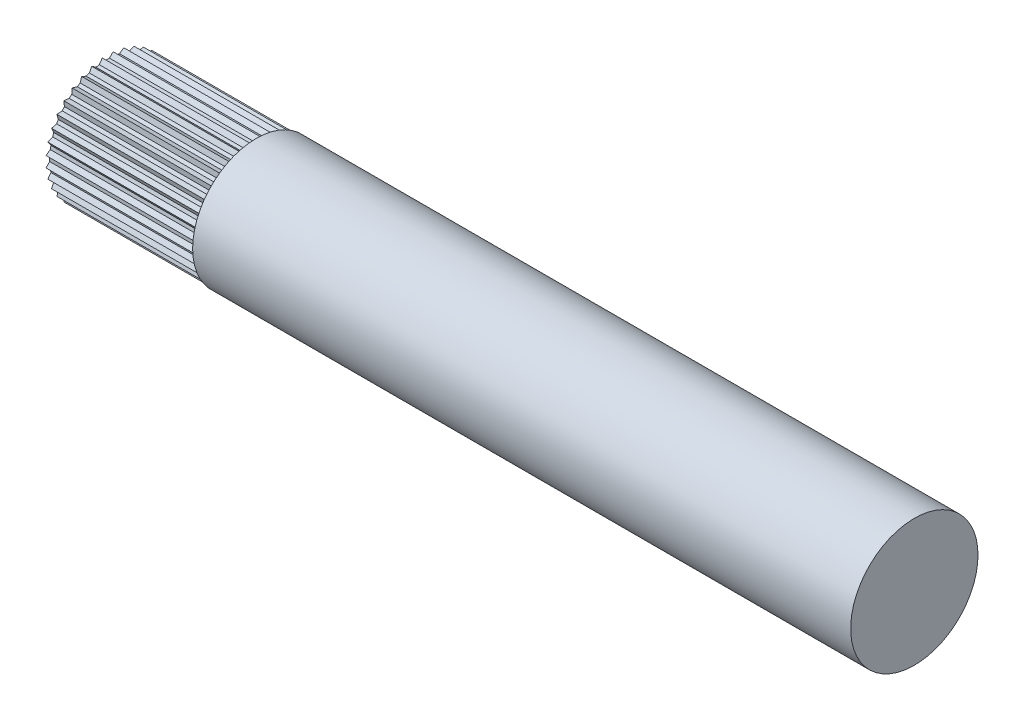
SolidWorks part; units mm, degrees
material "AISI 1015 Steel, Cold Drawn (SS)"
ref_plane "X-Y Datum" through (0, 0, 0) normal (0, 0, 1) x (1, 0, 0)
ref_plane "X-Z Datum" through (0, 0, 0) normal (0, 1, 0) x (1, 0, 0)
ref_plane "Y-Z Datum" through (0, 0, 0) normal (1, 0, 0) x (0, 0, -1)
sketch "Sketch1" plane through (0, 0, 0) normal (0, 1, 0) x (1, 0, 0)
  line L0 (139.925, 9.525) -> (139.925, 7.9375)
  line L1 (139.925, 7.9375) -> (19.25, 7.9375)
  line L2 (19.25, 7.9375) -> (19.25, 9.525)
  line L3 (19.25, 9.525) -> (139.925, 9.525)
  line L6 (157.324, 0) -> (-11.2643, 0) construction
  line L7 (19.25, 9.525) -> (19.25, -9.525) construction
  dimension "D1" = 1.5875
revolve "Revolve1" add sketch "Sketch1" angle 360 about L6
sketch "Sketch4" plane through (0, 0, 0) normal (1, 0, 0) x (0, 0, -1)
  line L0 (-9.2357, 0.808) -> (-8.6817, 0.254)
  line L1 (-8.6817, 0.254) -> (-8.6817, -0.254)
  line L2 (-8.6817, -0.254) -> (-9.2357, -0.808)
  line L3 (-8.6817, 0) -> (0, 0) construction
  line L4 (-8.5939, 1.2574) -> (-9.2357, 0.808)
  line L5 (-8.5057, 1.7577) -> (-8.5939, 1.2574)
  line L6 (-8.9551, 2.3995) -> (-8.5057, 1.7577)
  line L7 (-8.245, 2.7306) -> (-8.9551, 2.3995)
  line L8 (-8.0713, 3.208) -> (-8.245, 2.7306)
  line L9 (-8.4024, 3.9181) -> (-8.0713, 3.208)
  line L10 (-7.6456, 4.1209) -> (-8.4024, 3.9181)
  line L11 (-7.3916, 4.5608) -> (-7.6456, 4.1209)
  line L12 (-7.5944, 5.3176) -> (-7.3916, 4.5608)
  line L13 (-6.8138, 5.3859) -> (-7.5944, 5.3176)
  line L14 (-6.4873, 5.7751) -> (-6.8138, 5.3859)
  line L15 (-6.5556, 6.5556) -> (-6.4873, 5.7751)
  line L16 (-5.7751, 6.4873) -> (-6.5556, 6.5556)
  line L17 (-5.3859, 6.8138) -> (-5.7751, 6.4873)
  line L18 (-5.3176, 7.5944) -> (-5.3859, 6.8138)
  line L19 (-4.5608, 7.3916) -> (-5.3176, 7.5944)
  line L20 (-4.1209, 7.6456) -> (-4.5608, 7.3916)
  line L21 (-3.9181, 8.4024) -> (-4.1209, 7.6456)
  line L22 (-3.208, 8.0713) -> (-3.9181, 8.4024)
  line L23 (-2.7306, 8.245) -> (-3.208, 8.0713)
  line L24 (-2.3995, 8.9551) -> (-2.7306, 8.245)
  line L25 (-1.7577, 8.5057) -> (-2.3995, 8.9551)
  line L26 (-1.2574, 8.5939) -> (-1.7577, 8.5057)
  line L27 (-0.808, 9.2357) -> (-1.2574, 8.5939)
  line L28 (-0.254, 8.6817) -> (-0.808, 9.2357)
  line L29 (0.254, 8.6817) -> (-0.254, 8.6817)
  line L30 (0.808, 9.2357) -> (0.254, 8.6817)
  line L31 (1.2574, 8.5939) -> (0.808, 9.2357)
  line L32 (1.7577, 8.5057) -> (1.2574, 8.5939)
  line L33 (2.3995, 8.9551) -> (1.7577, 8.5057)
  line L34 (2.7306, 8.245) -> (2.3995, 8.9551)
  line L35 (3.208, 8.0713) -> (2.7306, 8.245)
  line L36 (3.9181, 8.4024) -> (3.208, 8.0713)
  line L37 (4.1209, 7.6456) -> (3.9181, 8.4024)
  line L38 (4.5608, 7.3916) -> (4.1209, 7.6456)
  line L39 (5.3176, 7.5944) -> (4.5608, 7.3916)
  line L40 (5.3859, 6.8138) -> (5.3176, 7.5944)
  line L41 (5.7751, 6.4873) -> (5.3859, 6.8138)
  line L42 (6.5556, 6.5556) -> (5.7751, 6.4873)
  line L43 (6.4873, 5.7751) -> (6.5556, 6.5556)
  line L44 (6.8138, 5.3859) -> (6.4873, 5.7751)
  line L45 (7.5944, 5.3176) -> (6.8138, 5.3859)
  line L46 (7.3916, 4.5608) -> (7.5944, 5.3176)
  line L47 (7.6456, 4.1209) -> (7.3916, 4.5608)
  line L48 (8.4024, 3.9181) -> (7.6456, 4.1209)
  line L49 (8.0713, 3.208) -> (8.4024, 3.9181)
  line L50 (8.245, 2.7306) -> (8.0713, 3.208)
  line L51 (8.9551, 2.3995) -> (8.245, 2.7306)
  line L52 (8.5057, 1.7577) -> (8.9551, 2.3995)
  line L53 (8.5939, 1.2574) -> (8.5057, 1.7577)
  line L54 (9.2357, 0.808) -> (8.5939, 1.2574)
  line L55 (8.6817, 0.254) -> (9.2357, 0.808)
  line L56 (8.6817, -0.254) -> (8.6817, 0.254)
  line L57 (9.2357, -0.808) -> (8.6817, -0.254)
  line L58 (8.5939, -1.2574) -> (9.2357, -0.808)
  line L59 (8.5057, -1.7577) -> (8.5939, -1.2574)
  line L60 (8.9551, -2.3995) -> (8.5057, -1.7577)
  line L61 (8.245, -2.7306) -> (8.9551, -2.3995)
  line L62 (8.0713, -3.208) -> (8.245, -2.7306)
  line L63 (8.4024, -3.9181) -> (8.0713, -3.208)
  line L64 (7.6456, -4.1209) -> (8.4024, -3.9181)
  line L65 (7.3916, -4.5608) -> (7.6456, -4.1209)
  line L66 (7.5944, -5.3176) -> (7.3916, -4.5608)
  line L67 (6.8138, -5.3859) -> (7.5944, -5.3176)
  line L68 (6.4873, -5.7751) -> (6.8138, -5.3859)
  line L69 (6.5556, -6.5556) -> (6.4873, -5.7751)
  line L70 (5.7751, -6.4873) -> (6.5556, -6.5556)
  line L71 (5.3859, -6.8138) -> (5.7751, -6.4873)
  line L72 (5.3176, -7.5944) -> (5.3859, -6.8138)
  line L73 (4.5608, -7.3916) -> (5.3176, -7.5944)
  line L74 (4.1209, -7.6456) -> (4.5608, -7.3916)
  line L75 (3.9181, -8.4024) -> (4.1209, -7.6456)
  line L76 (3.208, -8.0713) -> (3.9181, -8.4024)
  line L77 (2.7306, -8.245) -> (3.208, -8.0713)
  line L78 (2.3995, -8.9551) -> (2.7306, -8.245)
  line L79 (1.7577, -8.5057) -> (2.3995, -8.9551)
  line L80 (1.2574, -8.5939) -> (1.7577, -8.5057)
  line L81 (0.808, -9.2357) -> (1.2574, -8.5939)
  line L82 (0.254, -8.6817) -> (0.808, -9.2357)
  line L83 (-0.254, -8.6817) -> (0.254, -8.6817)
  line L84 (-0.808, -9.2357) -> (-0.254, -8.6817)
  line L85 (-1.2574, -8.5939) -> (-0.808, -9.2357)
  line L86 (-1.7577, -8.5057) -> (-1.2574, -8.5939)
  line L87 (-2.3995, -8.9551) -> (-1.7577, -8.5057)
  line L88 (-2.7306, -8.245) -> (-2.3995, -8.9551)
  line L89 (-3.208, -8.0713) -> (-2.7306, -8.245)
  line L90 (-3.9181, -8.4024) -> (-3.208, -8.0713)
  line L91 (-4.1209, -7.6456) -> (-3.9181, -8.4024)
  line L92 (-4.5608, -7.3916) -> (-4.1209, -7.6456)
  line L93 (-5.3176, -7.5944) -> (-4.5608, -7.3916)
  line L94 (-5.3859, -6.8138) -> (-5.3176, -7.5944)
  line L95 (-5.7751, -6.4873) -> (-5.3859, -6.8138)
  line L96 (-6.5556, -6.5556) -> (-5.7751, -6.4873)
  line L97 (-6.4873, -5.7751) -> (-6.5556, -6.5556)
  line L98 (-6.8138, -5.3859) -> (-6.4873, -5.7751)
  line L99 (-7.5944, -5.3176) -> (-6.8138, -5.3859)
  line L100 (-7.3916, -4.5608) -> (-7.5944, -5.3176)
  line L101 (-7.6456, -4.1209) -> (-7.3916, -4.5608)
  line L102 (-8.4024, -3.9181) -> (-7.6456, -4.1209)
  line L103 (-8.0713, -3.208) -> (-8.4024, -3.9181)
  line L104 (-8.245, -2.7306) -> (-8.0713, -3.208)
  line L105 (-8.9551, -2.3995) -> (-8.245, -2.7306)
  line L106 (-8.5057, -1.7577) -> (-8.9551, -2.3995)
  line L107 (-8.5939, -1.2574) -> (-8.5057, -1.7577)
  line L108 (-9.2357, -0.808) -> (-8.5939, -1.2574)
  circle A0 centre (0, 0) radius 8.6854 construction
  circle A1 centre (0, 0) radius 9.271 construction
  circle A2 centre (0, 0) radius 12.7
  point P155 (0, 0)
  dimension "D1" = 18.542
  dimension "D2" = 0.508
  dimension "D3" = 17.3708
  dimension "D6" = 25.4
  dimension "D4" = 135
  dimension "D5" = 1.616
  dimension "D7" = 36
extrude "Cut-Extrude2" cut sketch "Sketch4" along normal blind 22.225 from surface at 19.25 starting at face at (19.25, 0, -7.9375)
sketch "Sketch5" plane through (139.925, 0, 0) normal (1, 0, 0) x (0, 0, -1)
  circle A0 centre (0, 0) radius 7.9375
  dimension "D1" = 15.875
extrude "Boss-Extrude1" add sketch "Sketch5" against normal up to surface (120.675 mm away) up to face at (19.25, 0, 0)
